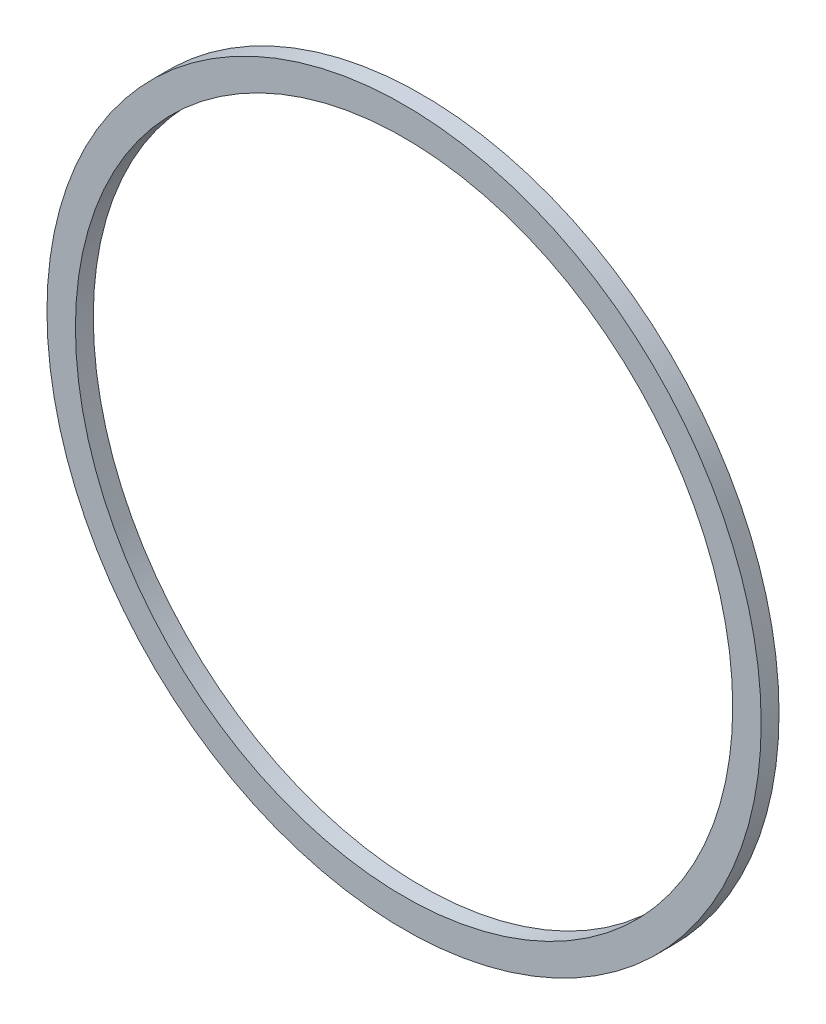
SolidWorks part; units mm, degrees
ref_plane "Front Plane" through (0, 0, 0) normal (0, 0, 1) x (1, 0, 0)
ref_plane "Top Plane" through (0, 0, 0) normal (0, 1, 0) x (1, 0, 0)
ref_plane "Right Plane" through (0, 0, 0) normal (1, 0, 0) x (0, 0, -1)
sketch "Sketch1" plane through (0, 0, 0) normal (0, 0, 1) x (1, 0, 0)
  circle A0 centre (0, 0) radius 127
  circle A1 centre (0, 0) radius 116.88
  dimension "D1" = 254
  dimension "D2" = 233.76
extrude "Boss-Extrude1" add sketch "Sketch1" along normal blind 6.35
